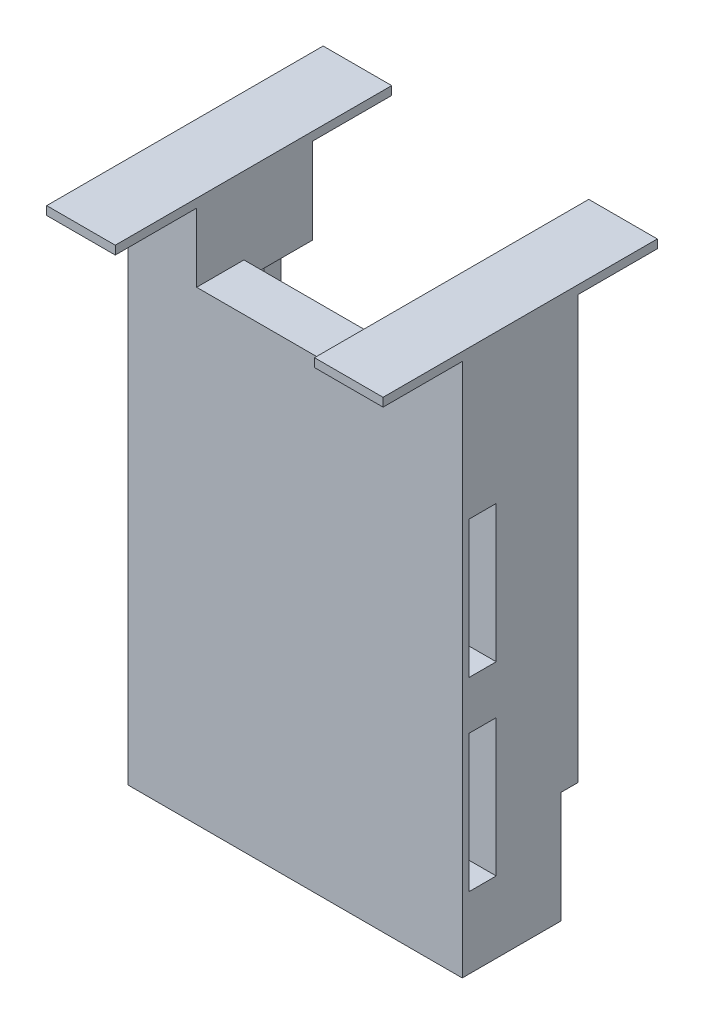
SolidWorks part; units mm, degrees
ref_plane "Front Plane" through (0, 0, 0) normal (0, 0, 1) x (1, 0, 0)
ref_plane "Top Plane" through (0, 0, 0) normal (0, 1, 0) x (1, 0, 0)
ref_plane "Right Plane" through (0, 0, 0) normal (1, 0, 0) x (0, 0, -1)
sketch "Sketch1" plane through (0, 0, 0) normal (0, 1, 0) x (1, 0, 0)
  line L0 (0, 0) -> (0, 60.439) construction
  line L1 (0, 0) -> (86.9706, 0) construction
  line L2 (-30.9499, -3.4771) -> (30.9499, -3.4771)
  line L4 (27.7749, 5.2859) -> (-27.7749, 5.2859)
  line L7 (-30.9499, 17.9859) -> (-24.0411, 17.9859)
  line L8 (-24.0411, 17.9859) -> (-24.0411, 14.8109)
  line L9 (-24.0411, 14.8109) -> (-27.7749, 14.8109)
  line L10 (-27.7749, 14.8109) -> (-27.7749, 5.2859)
  line L11 (24.0411, 14.8109) -> (27.7749, 14.8109)
  line L12 (27.7749, 14.8109) -> (27.7749, 5.2859)
  line L14 (30.9499, 17.9859) -> (24.0411, 17.9859)
  line L15 (24.0411, 17.9859) -> (24.0411, 14.8109)
  line L16 (-30.9499, 17.9859) -> (-30.9499, -3.4771)
  line L17 (30.9499, 17.9859) -> (30.9499, -3.4771)
  dimension "D1" = 61.8998
  dimension "D2" = 3.175
  dimension "D3" = 8.763
  dimension "D4" = 6.9088
  dimension "D5" = 27.7749
  dimension "D6" = 9.525
extrude "Boss-Extrude1" add sketch "Sketch1" along normal blind 83.0326 contours L14 L15 L11 L12 L4 L10 L9 L8 L7 L16 L2 L17
sketch "Sketch6" plane through (0, 83.0326, 0) normal (0, 1, 0) x (1, 0, 0)
  line L0 (-30.9499, 17.9859) -> (-30.9499, -3.4771)
  line L1 (-30.9499, -3.4771) -> (30.9499, -3.4771)
  line L2 (30.9499, -3.4771) -> (30.9499, 17.9859)
  line L3 (30.9499, 17.9859) -> (-30.9499, 17.9859)
extrude "Boss-Extrude3" add sketch "Sketch6" along normal blind 3.175
sketch "Sketch7" plane through (0, 83.0326, 0) normal (0, -1, 0) x (1, 0, 0)
  line L0 (0, -5.2859) -> (0, -14.8109) construction
  line L1 (27.7749, -5.2859) -> (-27.7749, -5.2859) construction
  line L2 (-8.2677, -5.2859) -> (-8.2677, -14.8109)
  line L3 (8.2677, -5.2859) -> (8.2677, -14.8109)
  line L4 (8.2677, -14.8109) -> (-8.2677, -14.8109)
  line L5 (8.2677, -5.2859) -> (-8.2677, -5.2859)
  dimension "D1" = 9.525
  dimension "D2" = 8.2677
  dimension "D3" = 8.2677
extrude "Cut-Extrude2" cut sketch "Sketch7" against normal through all
sketch "Sketch8" plane through (-30.9499, 0, 0) normal (-1, 0, 0) x (0, 0, 1)
  line L0 (-17.9859, 43.1038) -> (3.4771, 43.1038) construction
  line L1 (-17.9859, 86.2076) -> (-17.9859, 0) construction
  line L2 (3.4771, 86.2076) -> (3.4771, 0) construction
  line L4 (2.2655, 13.224) -> (2.2655, 38.624)
  line L6 (-0.4599, 43.1038) -> (-0.4599, 24.0538) construction
  line L7 (2.2655, 13.224) -> (-2.8145, 13.224)
  line L8 (2.2655, 72.9836) -> (-2.8145, 72.9836)
  line L9 (2.2655, 72.9836) -> (2.2655, 47.5836)
  line L10 (2.2655, 47.5836) -> (-2.8145, 47.5836)
  line L11 (-2.8145, 72.9836) -> (-2.8145, 47.5836)
  line L14 (-2.8145, 13.224) -> (-2.8145, 38.624)
  line L15 (2.2655, 38.624) -> (-2.8145, 38.624)
  point P8 (2.2655, 60.2836)
  point P21 (2.2655, 25.924)
  dimension "D3" = 5.08
  dimension "D4" = 25.4
extrude "Cut-Extrude3" cut sketch "Sketch8" against normal through all contours L8 L11 L10 L9 | L4 L15 L14 L7
sketch "Sketch14" plane through (0, 0, 0) normal (0, -1, 0) x (1, 0, 0)
  line L0 (-27.7749, -5.2859) -> (-30.9499, -5.2859) construction
  line L1 (-30.9499, -17.9859) -> (-30.9499, 3.4771) construction
sketch "Sketch15" plane through (0, 0, -17.9859) normal (0, 0, -1) x (-1, 0, 0)
  line L0 (-30.9499, 0) -> (30.9499, 0)
  line L1 (-30.9499, 20.6324) -> (30.9499, 20.6324)
  line L2 (-30.9499, 20.6324) -> (-30.9499, 0)
  line L3 (30.9499, 0) -> (30.9499, 20.6324)
  dimension "D1" = 20.6324
extrude "Cut-Extrude4" cut sketch "Sketch15" against normal blind 3.175
sketch "Sketch16" plane through (0, 86.2076, 0) normal (0, 1, 0) x (1, 0, 0)
  line L1 (30.9499, 17.9859) -> (-30.9499, 17.9859) construction
  line L2 (0, 17.9859) -> (0, 5.2859) construction
  line L3 (8.2677, 5.2859) -> (-8.2677, 5.2859) construction
  line L6 (-18.2499, 17.9859) -> (-18.2499, 5.2859)
  line L7 (-18.2499, 5.2859) -> (18.2499, 5.2859)
  line L8 (18.2499, 5.2859) -> (18.2499, 17.9859)
  line L9 (-18.2499, 17.9859) -> (18.2499, 17.9859)
extrude "Cut-Extrude5" cut sketch "Sketch16" against normal blind 3.175
sketch "Sketch17" plane through (0, 86.2076, 0) normal (0, 1, 0) x (1, 0, 0)
  line L0 (-30.9499, 17.9859) -> (-30.9499, -3.4771)
  line L1 (-30.9499, -3.4771) -> (-18.2499, -3.4771)
  line L2 (-30.9499, -3.4771) -> (30.9499, -3.4771) construction
  line L3 (-18.2499, -3.4771) -> (-18.2499, 17.9859)
  line L4 (-18.2499, 17.9859) -> (-30.9499, 17.9859)
  line L5 (18.2499, 17.9859) -> (18.2499, -3.4771)
  line L6 (18.2499, -3.4771) -> (30.9499, -3.4771)
  line L7 (30.9499, -3.4771) -> (30.9499, 17.9859)
  line L8 (30.9499, 17.9859) -> (18.2499, 17.9859)
extrude "Boss-Extrude4" add sketch "Sketch17" along normal blind 12.7
sketch "Sketch18" plane through (0, 98.9076, 0) normal (0, 1, 0) x (1, 0, 0)
  line L0 (30.9499, 7.2544) -> (18.2499, 7.2544) construction
  line L1 (30.9499, -3.4771) -> (30.9499, 17.9859) construction
  line L2 (18.2499, 17.9859) -> (18.2499, -3.4771) construction
  line L3 (30.9499, 32.6544) -> (18.2499, 32.6544)
  line L4 (30.9499, -18.1456) -> (18.2499, -18.1456)
  line L5 (18.2499, 32.6544) -> (18.2499, -18.1456)
  line L6 (30.9499, -18.1456) -> (30.9499, 32.6544)
  dimension "D1" = 25.4
  dimension "D2" = 25.4
extrude "Boss-Extrude5" add sketch "Sketch18" along normal blind 1.5875
sketch "Sketch19" plane through (0, 98.9076, 0) normal (0, 1, 0) x (1, 0, 0)
  line L0 (-30.9499, 7.2544) -> (-18.2499, 7.2544) construction
  line L1 (-30.9499, 17.9859) -> (-30.9499, -3.4771) construction
  line L2 (-18.2499, -3.4771) -> (-18.2499, 17.9859) construction
  line L3 (-30.9499, -18.5537) -> (-18.2499, -18.5537)
  line L4 (-30.9499, 32.6544) -> (-18.2499, 32.6544)
  line L5 (-30.9499, 32.6544) -> (-30.9499, -18.5537)
  line L7 (-18.2499, -18.5537) -> (-18.2499, 32.6544)
  dimension "D2" = 25.4
extrude "Boss-Extrude6" add sketch "Sketch19" along normal blind 1.5875
equation "\"1.0921.1120754in\"=1.11208"
equation "\"0.0625in..6690\"=0.0625"
